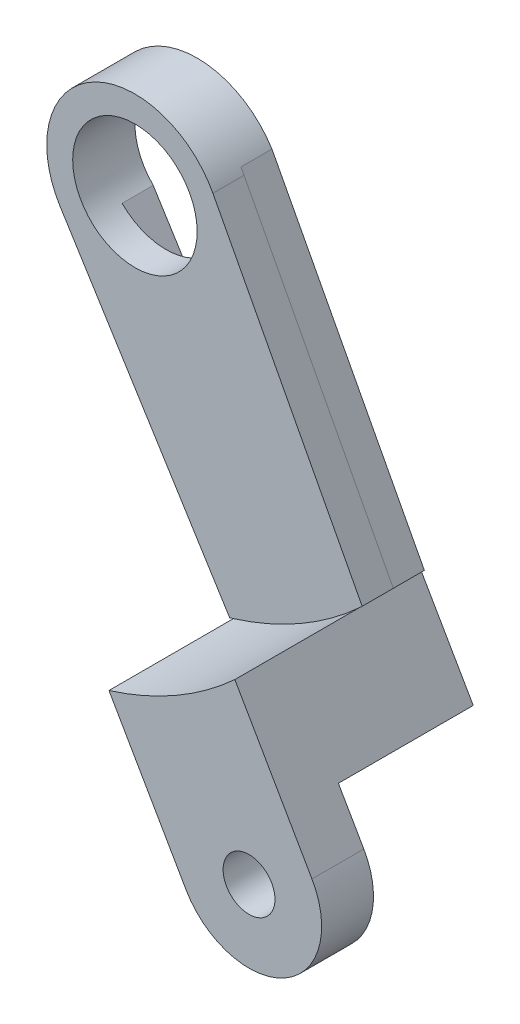
SolidWorks part; units mm, degrees
ref_plane "Ebene vorne" through (0, 0, 0) normal (0, 0, 1) x (1, 0, 0)
ref_plane "Ebene oben" through (0, 0, 0) normal (0, 1, 0) x (1, 0, 0)
ref_plane "Ebene rechts" through (0, 0, 0) normal (1, 0, 0) x (0, 0, -1)
sketch "Skizze1" plane through (0, 0, 0) normal (0, 0, 1) x (1, 0, 0)
  line L0 (-6.0683, -3.4893) -> (-13.5036, 9.4416)
  line L1 (0, 0) -> (-23, 40) construction
  line L2 (6.0683, 3.4893) -> (-1.3669, 16.4202)
  circle A0 centre (0, 0) radius 2.5
  circle A1 centre (0, 0) radius 7
  circle A2 centre (-23, 40) radius 32
  dimension "D1" = 5
  dimension "D2" = 14
  dimension "D3" = 64
  dimension "D4" = 23
  dimension "D5" = 40
extrude "Aufsatz-Linear austragen1" add sketch "Skizze1" along normal blind 5
sketch "Skizze2" plane through (0, 0, 0) normal (0, 0, -1) x (-1, 0, 0)
  line L0 (13.5036, 9.4416) -> (1.3669, 16.4202)
  line L1 (6.0683, -3.4893) -> (13.5036, 9.4416) construction
  line L2 (1.3669, 16.4202) -> (-3.6178, 7.7511)
  line L3 (-6.0683, 3.4893) -> (1.3669, 16.4202) construction
  line L4 (-3.6178, 7.7511) -> (8.5189, 0.7725)
  line L5 (8.5189, 0.7725) -> (13.5036, 9.4416)
  circle A0 centre (23, 40) radius 32
  line M6 (6.0683, -3.4893) -> (13.5036, 9.4416)
  arc M7 (13.5036, 9.4416) -> (1.3669, 16.4202) centre (23, 40) cw
  line M8 (1.3669, 16.4202) -> (-6.0683, 3.4893)
  dimension "D1" = 10
extrude "Aufsatz-Linear austragen2" add sketch "Skizze2" along normal offset from surface (7 mm away) 1 contours L4 M8 M6 M7
sketch "Skizze3" plane through (0, 0, -7) normal (0, 0, -1) x (-1, 0, 0)
  line L0 (-3.6178, 7.7511) -> (15.4816, 43.9652)
  line L1 (8.5189, 0.7725) -> (30.2091, 35.4969)
  circle A0 centre (23, 40) radius 32
  circle A2 centre (23, 40) radius 6
  arc A3 (1.3669, 16.4202) -> (13.5036, 9.4416) centre (23, 40) ccw construction
  circle A4 centre (23, 40) radius 8.5
  dimension "D1" = 17
  dimension "D2" = 12
extrude "Aufsatz-Linear austragen3" add sketch "Skizze3" along normal blind 3
sketch "Sketch1" plane through (0, 0, -10) normal (0, 0, -1) x (-1, 0, 0)
  line L0 (30.2091, 35.4969) -> (8.5189, 0.7725)
  line L1 (8.5189, 0.7725) -> (13.5036, 9.4416) construction
  line L2 (-3.6178, 7.7511) -> (8.5189, 0.7725) construction
  line L3 (8.5189, 0.7725) -> (-3.6178, 7.7511)
  line L5 (-3.6178, 7.7511) -> (15.7909, 44.5031)
  line L6 (15.7909, 44.5031) -> (30.2091, 35.4969) construction
  line L7 (18.043, 43.0964) -> (-1.3204, 6.4301)
  line L8 (27.957, 36.9036) -> (6.2154, 2.097)
  circle A0 centre (23, 40) radius 5.8446
  circle A1 centre (23, 40) radius 8.5
  circle M8 centre (23, 40) radius 6
  arc M9 (30.2091, 35.4969) -> (15.4816, 43.9652) centre (23, 40) ccw
  arc M11 (1.0899, 16.6773) -> (1.3669, 16.4202) centre (23, 40) ccw
  line M12 (1.3669, 16.4202) -> (-3.6178, 7.7511)
  line M13 (-3.6178, 7.7511) -> (8.5189, 0.7725)
  line M14 (8.5189, 0.7725) -> (13.5036, 9.4416)
  arc M15 (13.5036, 9.4416) -> (13.8652, 9.3315) centre (23, 40) ccw
  line M16 (13.8652, 9.3315) -> (30.2091, 35.4969)
extrude "Boss-Extrude1" add sketch "Sketch1" along normal blind 3 contours L6 L8 A1 M8 | A1 L8 M13 M14 M15 M16 | L6 M9 M8 | L6 L5 A1 L7 M8 | A1 L5 L7 M11 M12 M13
